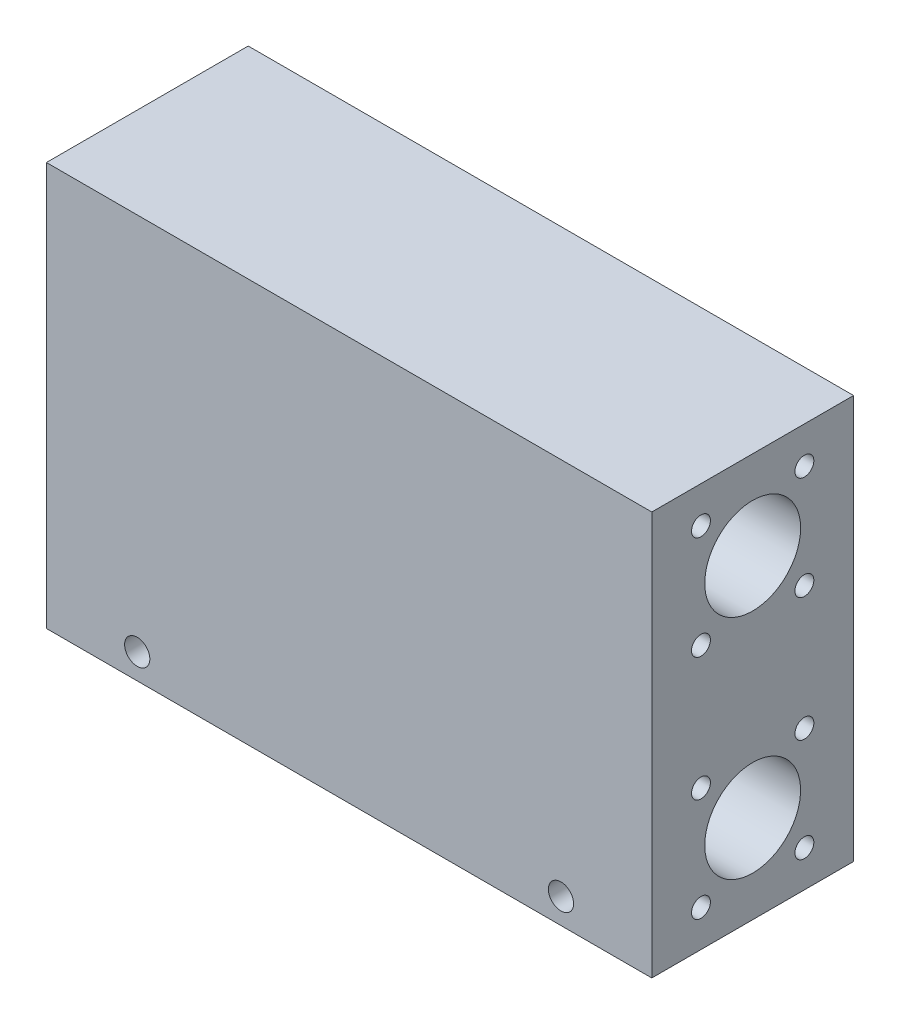
SolidWorks part; units mm, degrees
material "1060 Alloy"
ref_plane "Front Plane" through (0, 0, 0) normal (0, 0, 1) x (1, 0, 0)
ref_plane "Top Plane" through (0, 0, 0) normal (0, 1, 0) x (1, 0, 0)
ref_plane "Right Plane" through (0, 0, 0) normal (1, 0, 0) x (0, 0, -1)
sketch "Sketch1" plane through (0, 0, 0) normal (0, 0, 1) x (1, 0, 0)
  line L1 (0, 0) -> (120, 0)
  line L2 (0, 0) -> (0, 80)
  line L3 (0, 80) -> (120, 80)
  line L4 (120, 0) -> (120, 80)
  dimension "D1" = 80
  dimension "D2" = 120
extrude "Boss-Extrude1" add sketch "Sketch1" along normal blind 40 contours L3 L4 L1 L2
sketch "Sketch2" plane through (0, 0, 0) normal (-1, 0, 0) x (0, 0, 1)
  line L0 (20, 80) -> (20, 0) construction
  line L1 (40, 80) -> (0, 80) construction
  line L2 (40, 0) -> (0, 0) construction
  line L3 (40, 40) -> (0, 40) construction
  line L4 (40, 0) -> (40, 80) construction
  line L5 (0, 0) -> (0, 80) construction
  line L6 (0, 62.5) -> (40, 62.5) construction
  line L7 (0, 17.5) -> (40, 17.5) construction
  circle A1 centre (30.25, 72.75) radius 1.85
  circle A2 centre (9.75, 72.75) radius 1.85
  circle A3 centre (30.25, 52.25) radius 1.85
  circle A4 centre (9.75, 52.25) radius 1.85
  circle A5 centre (9.75, 27.75) radius 1.85
  circle A6 centre (30.25, 27.75) radius 1.85
  circle A7 centre (30.25, 7.25) radius 1.85
  circle A9 centre (9.75, 7.25) radius 1.85
  dimension "D4" = 3.7
  dimension "D1" = 22.5
  dimension "D2" = 9.75
  dimension "D3" = 7.25
extrude "linear-bearing-screw-cuts" cut sketch "Sketch2" against normal blind 14
sketch "Sketch3" plane through (0, 0, 0) normal (-1, 0, 0) x (0, 0, 1)
  line L0 (20, 80) -> (20, 0) construction
  line L1 (40, 80) -> (0, 80) construction
  line L2 (40, 0) -> (0, 0) construction
  line L3 (0, 40) -> (40, 40) construction
  line L4 (0, 0) -> (0, 80) construction
  line L5 (40, 0) -> (40, 80) construction
  line L6 (0, 62.5) -> (40, 62.5) construction
  line L7 (0, 17.5) -> (40, 17.5) construction
  circle A0 centre (20, 62.5) radius 9.5
  circle A2 centre (20, 17.5) radius 9.5
  dimension "D2" = 19
  dimension "D1" = 45
extrude "linear-bearings-hole" cut sketch "Sketch3" against normal blind 55
sketch "Sketch4" plane through (120, 0, 0) normal (1, 0, 0) x (0, 0, -1)
  line L0 (-20, 80) -> (-20, 0) construction
  line L1 (-40, 80) -> (0, 80) construction
  line L2 (-40, 0) -> (0, 0) construction
  line L3 (-40, 40) -> (0, 40) construction
  line L4 (-40, 0) -> (-40, 80) construction
  line L5 (0, 0) -> (0, 80) construction
  line L6 (-40, 62.5) -> (0, 62.5) construction
  line L7 (-40, 17.5) -> (0, 17.5) construction
  circle A0 centre (-9.75, 72.75) radius 1.875
  circle A1 centre (-30.25, 72.75) radius 1.875
  circle A2 centre (-9.75, 52.25) radius 1.875
  circle A3 centre (-30.25, 52.25) radius 1.875
  circle A4 centre (-30.25, 27.75) radius 1.875
  circle A5 centre (-9.75, 27.75) radius 1.875
  circle A6 centre (-9.75, 7.25) radius 1.875
  circle A7 centre (-30.25, 7.25) radius 1.875
  dimension "D2" = 3.75
  dimension "D1" = 45
  dimension "D3" = 7.25
  dimension "D4" = 9.75
extrude "linear-bearing-screw-cuts2" cut sketch "Sketch4" against normal blind 14
sketch "Sketch5" plane through (120, 0, 0) normal (1, 0, 0) x (0, 0, -1)
  line L0 (-20, 80) -> (-20, 0) construction
  line L1 (-40, 80) -> (0, 80) construction
  line L2 (-40, 0) -> (0, 0) construction
  line L3 (0, 40) -> (-40, 40) construction
  line L4 (0, 0) -> (0, 80) construction
  line L5 (-40, 0) -> (-40, 80) construction
  line L6 (-40, 62.5) -> (0, 62.5) construction
  line L7 (-40, 17.5) -> (0, 17.5) construction
  circle A0 centre (-20, 62.5) radius 9.5
  circle A1 centre (-20, 17.5) radius 9.5
  dimension "D2" = 19
  dimension "D1" = 45
extrude "Cut-Extrude4" cut sketch "Sketch5" against normal blind 55
sketch "Sketch11" plane through (65, 0, 0) normal (1, 0, 0) x (0, 0, -1)
  circle A0 centre (-20, 62.5) radius 6
  circle A1 centre (-20, 17.5) radius 6
  dimension "D1" = 12
extrude "Cut-Extrude9" cut sketch "Sketch11" against normal through all
sketch "Sketch12" plane through (0, 0, 40) normal (0, 0, 1) x (1, 0, 0)
  line L0 (120, 0) -> (120, 80) construction
  line L1 (0, 0) -> (0, 80) construction
  line L2 (0, 80) -> (120, 80) construction
  circle A0 centre (5.5, 74.5) radius 1.25
  circle A1 centre (36.5, 74.5) radius 1.25
  circle A2 centre (83.5, 74.5) radius 1.25
  circle A3 centre (114.5, 74.5) radius 1.25
  circle A4 centre (5.5, 43.5) radius 1.25
  circle A5 centre (36.5, 43.5) radius 1.25
  circle A6 centre (83.5, 43.5) radius 1.25
  circle A7 centre (114.5, 43.5) radius 1.25
  dimension "D4" = 2.5
  dimension "D1" = 31
  dimension "D2" = 31
  dimension "D3" = 31
  dimension "D5" = 5.5
  dimension "D6" = 5.5
  dimension "D7" = 5.5
extrude "Cut-Extrude10" [suppressed] cut sketch "Sketch12" against normal through all
sketch "Sketch13" plane through (0, 0, 0) normal (0, 0, -1) x (-1, 0, 0)
  line L1 (-120, 0) -> (-120, 80) construction
  line L2 (0, 0) -> (0, 80) construction
  line L3 (0, 0) -> (-120, 0) construction
  circle A0 centre (-102, 5) radius 2.5
  circle A1 centre (-18, 5) radius 2.5
  dimension "D3" = 5
  dimension "D4" = 18
  dimension "D1" = 5
  dimension "D2" = 18
extrude "Cut-Extrude11" cut sketch "Sketch13" against normal through all
